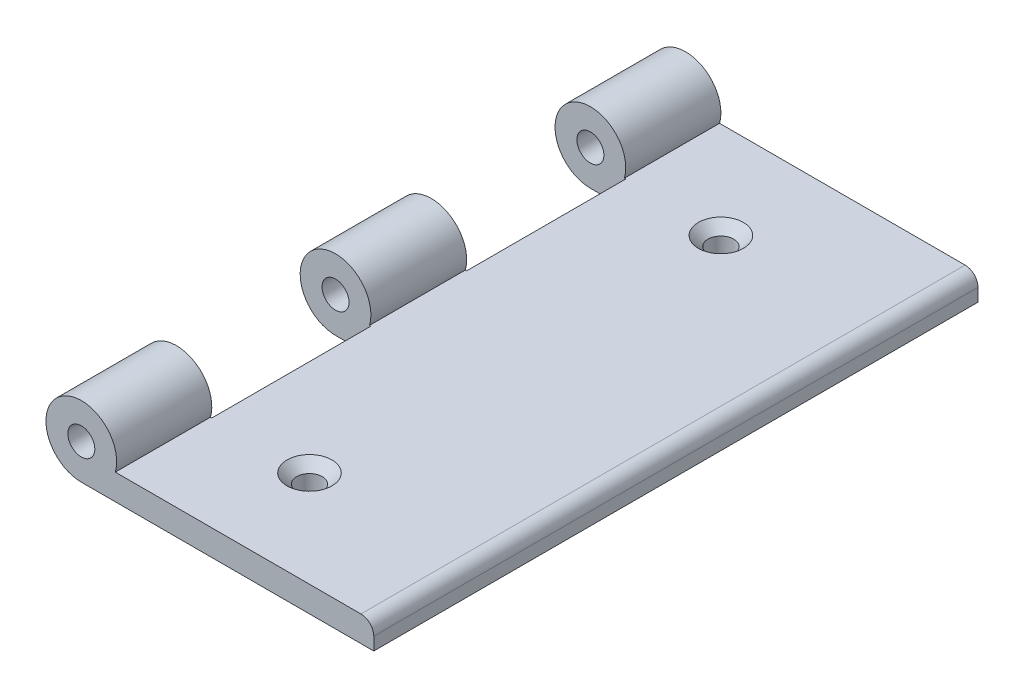
SolidWorks part; units mm, degrees
ref_plane "Front" through (0, 0, 0) normal (0, 0, 1) x (1, 0, 0)
ref_plane "Top" through (0, 0, 0) normal (0, 1, 0) x (1, 0, 0)
ref_plane "Right" through (0, 0, 0) normal (1, 0, 0) x (0, 0, -1)
sketch "Эскиз1" plane through (0, 0, 0) normal (0, 1, 0) x (1, 0, 0)
  line L1 (-20, 47) -> (20, 47)
  line L2 (-20, 47) -> (-20, -47)
  line L3 (-20, -47) -> (20, -47)
  line L4 (20, 47) -> (20, -47)
  line L5 (-20, 47) -> (20, -47) construction
  line L6 (-20, -47) -> (20, 47) construction
  point P0 (0, 0)
  dimension "D1" = 94
  dimension "D2" = 40
extrude "Бобышка-Вытянуть1" add sketch "Эскиз1" along normal blind 4
sketch "Эскиз2" plane through (0, 0, 0) normal (0, 0, 1) x (1, 0, 0)
  line L0 (-20, 4) -> (-20, 0) construction
  line L1 (-20, 0) -> (20, 0) construction
  line L3 (-20, 0) -> (-25.5, 0)
  line L4 (-20, 0) -> (-20, 4)
  line L5 (-20, 4) -> (-20.2085, 4)
  arc A0 (-20.2085, 4) -> (-25.5, 0) centre (-25.5, 5.5) ccw
  circle A1 centre (-25.5, 5.5) radius 2.1
  dimension "D1" = 11
  dimension "D2" = 4.2
extrude "Бобышка-Вытянуть2" add sketch "Эскиз2" along normal up to vertex (47 mm away) and the other way up to vertex (47 mm away)
sketch "Эскиз3" plane through (0, 0, 0) normal (0, 1, 0) x (1, 0, 0)
  line L0 (-36.8294, 0) -> (-8.257, 0) construction
  line L1 (-25.5, 50.4404) -> (-25.5, -51.3176) construction
  line L2 (-31, 47) -> (-31, -47) construction
  line L3 (-31, 32.2) -> (-20, 32.2)
  line L4 (-31, 32.2) -> (-31, 7.45)
  line L5 (-31, 7.45) -> (-20, 7.45)
  line L6 (-20, 32.2) -> (-20, 7.45)
  line L7 (-20, -47) -> (-20, 47) construction
  line L8 (-23.4, 47) -> (-27.6, 47) construction
  line L9 (-31, -7.45) -> (-20, -7.45)
  line L10 (-31, -7.45) -> (-31, -32.2)
  line L11 (-31, -32.2) -> (-20, -32.2)
  line L12 (-20, -7.45) -> (-20, -32.2)
  line L13 (-31, -47) -> (-20, -47) construction
  dimension "D1" = 14.8
  dimension "D2" = 7.45
  dimension "D3" = 7.45
  dimension "D4" = 14.8
extrude "Вырез-Вытянуть1" cut sketch "Эскиз3" along normal blind 14
sketch "Эскиз4" plane through (0, 4, 0) normal (0, 1, 0) x (1, 0, 0)
  line L0 (-20, 32.2) -> (-20, 7.45) construction
  line L1 (-20, -7.45) -> (-20, -32.2) construction
  line L2 (20, 47) -> (-20.2085, 47) construction
  line L3 (-20.2085, -47) -> (20, -47) construction
  circle A0 centre (-5, 32) radius 2
  circle A1 centre (-5, -32) radius 2
  dimension "D1" = 4
  dimension "D2" = 4
  dimension "D3" = 15
  dimension "D4" = 15
  dimension "D5" = 15
  dimension "D6" = 15
extrude "Вырез-Вытянуть2" cut sketch "Эскиз4" against normal blind 14
chamfer "Фаска2" distance 1.5 angle 45 2 edges at (-5, 4, 34) (-5, 4, -30)
fillet "Скругление1" radius 2 1 edges at (20, 4, 0)
